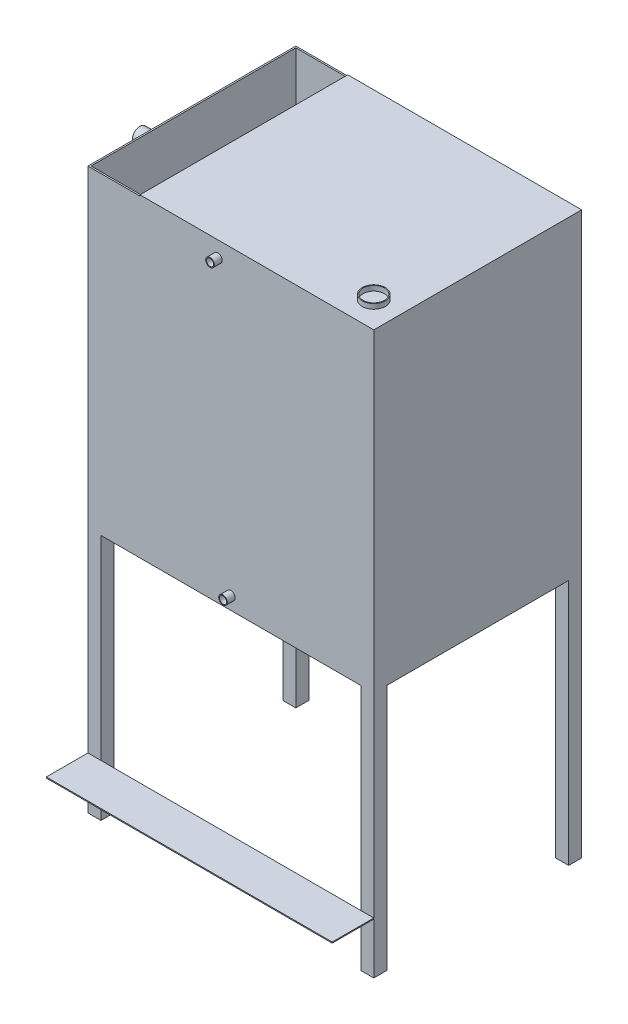
SolidWorks part; units mm, degrees
ref_plane "Спереди" through (0, 0, 0) normal (0, 0, 1) x (1, 0, 0)
ref_plane "Сверху" through (0, 0, 0) normal (0, 1, 0) x (1, 0, 0)
ref_plane "Справа" through (0, 0, 0) normal (1, 0, 0) x (0, 0, -1)
sketch "Эскиз1" plane through (0, 0, 0) normal (0, 1, 0) x (1, 0, 0)
  line L1 (0, 0) -> (1100, 0)
  line L2 (0, 0) -> (0, 800)
  line L3 (0, 800) -> (1100, 800)
  line L4 (1100, 0) -> (1100, 800)
  dimension "D1" = 1100
  dimension "D2" = 800
extrude "Бобышка-Вытянуть1" add sketch "Эскиз1" along normal blind 6
sketch "Эскиз3" plane through (0, 6, 0) normal (0, 1, 0) x (1, 0, 0)
  line L1 (0, 0) -> (1100, 0)
  line L2 (0, 0) -> (0, 800)
  line L3 (0, 800) -> (1100, 800)
  line L4 (1100, 0) -> (1100, 800)
  line L5 (6, 794) -> (1094, 794)
  line L6 (6, 794) -> (6, 6)
  line L7 (6, 6) -> (1094, 6)
  line L8 (1094, 794) -> (1094, 6)
  dimension "D1" = 6
  dimension "D2" = 6
  dimension "D3" = 6
  dimension "D4" = 6
extrude "Бобышка-Вытянуть2" add sketch "Эскиз3" along normal blind 1200
sketch "Эскиз4" plane through (0, 1206, 0) normal (0, 1, 0) x (1, 0, 0)
  line L1 (200, 0) -> (1100, 0)
  line L2 (200, 0) -> (200, 800)
  line L3 (200, 800) -> (1100, 800)
  line L4 (1100, 0) -> (1100, 800)
  line L6 (1100, 800) -> (0, 800) construction
  dimension "D1" = 900
extrude "Бобышка-Вытянуть3" add sketch "Эскиз4" along normal blind 4
sketch "Эскиз5" plane through (0, 0, 0) normal (0, -1, 0) x (1, 0, 0)
  line L0 (1050, 0) -> (1100, 0)
  line L1 (0, 0) -> (50, 0)
  line L2 (0, 0) -> (0, -50)
  line L3 (0, -50) -> (50, -50)
  line L4 (50, 0) -> (50, -50)
  line L5 (1050, 0) -> (1050, -50)
  line L6 (1050, -50) -> (1100, -50)
  line L7 (1100, 0) -> (1100, -50)
  line L8 (1050, -750) -> (1100, -750)
  line L9 (1050, -750) -> (1050, -800)
  line L10 (1050, -800) -> (1100, -800)
  line L11 (1100, -750) -> (1100, -800)
  line L12 (0, -750) -> (50, -750)
  line L13 (0, -750) -> (0, -800)
  line L14 (0, -800) -> (50, -800)
  line L15 (50, -750) -> (50, -800)
  dimension "D1" = 50
  dimension "D2" = 2
  dimension "D3" = 2
extrude "Бобышка-Вытянуть4" add sketch "Эскиз5" along normal blind 950
sketch "Эскиз6" plane through (0, 1210, 0) normal (0, 1, 0) x (1, 0, 0)
  line L1 (200, 0) -> (1100, 0) construction
  line L2 (1100, 0) -> (1100, 800) construction
  circle A0 centre (1000, 100) radius 44.5
  circle A1 centre (1000, 100) radius 41
  dimension "D1" = 89
  dimension "D2" = 100
  dimension "D3" = 100
  dimension "D4" = 3.5
extrude "Бобышка-Вытянуть5" add sketch "Эскиз6" along normal blind 19 and the other way blind 800
sketch "Эскиз7" plane through (0, 0, 0) normal (-1, 0, 0) x (0, 0, 1)
  line L0 (-800, 1210) -> (0, 1210) construction
  line L1 (-800, 1206) -> (-800, -950) construction
  circle A0 centre (-250, 1160) radius 28.5
  circle A1 centre (-250, 1160) radius 25
  dimension "D1" = 50
  dimension "D2" = 57
  dimension "D3" = 550
  dimension "D4" = 3.5
extrude "Бобышка-Вытянуть6" add sketch "Эскиз7" along normal blind 50
sketch "Эскиз8" plane through (0, 0, 0) normal (0, -1, 0) x (1, 0, 0)
  line L0 (0, -750) -> (0, -50) construction
  line L1 (50, 0) -> (1050, 0) construction
  circle A0 centre (171.2, -100) radius 16.75
  circle A1 centre (171.2, -100) radius 13.55
  dimension "D1" = 171.2
  dimension "D2" = 33.5
  dimension "D3" = 100
  dimension "D4" = 3.2
extrude "Бобышка-Вытянуть7" add sketch "Эскиз8" along normal blind 50 and the other way blind 50
sketch "Эскиз9" plane through (0, 0, 0) normal (0, -1, 0) x (1, 0, 0)
  line L0 (1050, -800) -> (50, -800) construction
  line L1 (0, -750) -> (0, -50) construction
  circle A0 centre (300, -250) radius 21.15
  circle A1 centre (300, -250) radius 17.95
  dimension "D1" = 42.3
  dimension "D2" = 550
  dimension "D3" = 300
  dimension "D4" = 3.2
extrude "Бобышка-Вытянуть8" add sketch "Эскиз9" along normal blind 49
sketch "Эскиз10" plane through (0, 0, 0) normal (0, 0, 1) x (1, 0, 0)
  line L0 (200, 1210) -> (1100, 1210) construction
  line L1 (0, 1206) -> (0, -950) construction
  circle A0 centre (500, 1150) radius 16.75
  circle A1 centre (500, 1150) radius 13.55
  dimension "D1" = 33.5
  dimension "D2" = 3.2
  dimension "D3" = 60
  dimension "D4" = 500
extrude "Бобышка-Вытянуть9" add sketch "Эскиз10" along normal blind 30
sketch "Эскиз11" plane through (0, 0, 0) normal (0, 0, 1) x (1, 0, 0)
  line L0 (0, 1206) -> (0, -950) construction
  line L1 (0, -800) -> (-160, -800)
  line L2 (0, -800) -> (0, -804)
  line L3 (0, -804) -> (-160, -804)
  line L4 (-160, -800) -> (-160, -804)
  line L5 (50, -950) -> (0, -950) construction
  dimension "D1" = 4
  dimension "D2" = 150
  dimension "D3" = 160
extrude "Бобышка-Вытянуть10" [suppressed] add sketch "Эскиз11" against normal up to surface (800 mm away)
sketch "Эскиз12" [suppressed] plane through (0, 0, 0) normal (0, 0, 1) x (1, 0, 0)
  line L0 (-40, -804) -> (0, -804)
  line L1 (0, -804) -> (0, -844)
  line L2 (0, -844) -> (-4, -844)
  line L3 (-4, -844) -> (-4, -808)
  line L4 (-4, -808) -> (-40, -808)
  line L5 (-40, -808) -> (-40, -804)
  line L6 (0, -804) -> (0, -950) construction
  line L7 (-160, -804) -> (0, -804) construction
  dimension "D1" = 40
  dimension "D2" = 40
  dimension "D3" = 4
  dimension "D4" = 4
extrude "Бобышка-Вытянуть11" [suppressed] add sketch "Эскиз12" against normal up to surface (800 mm away)
sketch "Эскиз13" plane through (0, 0, 0) normal (0, 0, 1) x (1, 0, 0)
  line L0 (0, 1206) -> (0, -950) construction
  line L1 (0, -750) -> (1100, -750)
  line L2 (0, -750) -> (0, -754)
  line L3 (0, -754) -> (1100, -754)
  line L4 (1100, -750) -> (1100, -754)
  line L5 (1100, 1210) -> (1100, -950) construction
  line L6 (50, -950) -> (0, -950) construction
  dimension "D1" = 4
  dimension "D2" = 200
extrude "Бобышка-Вытянуть12" add sketch "Эскиз13" along normal blind 160
sketch "Эскиз14" plane through (0, 0, 0) normal (0, 0, 1) x (1, 0, 0)
  line L0 (50, 0) -> (1050, 0) construction
  line L1 (0, 1206) -> (0, -750) construction
  circle A0 centre (550, 50) radius 13.55
  circle A1 centre (550, 50) radius 16.75
  dimension "D1" = 3.2
  dimension "D2" = 33.5
  dimension "D3" = 50
  dimension "D4" = 550
extrude "Бобышка-Вытянуть13" add sketch "Эскиз14" along normal blind 30
